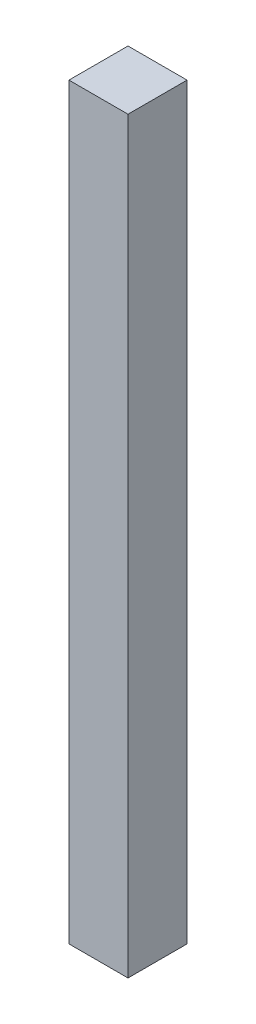
SolidWorks part; units mm, degrees
ref_plane "Front Plane" through (0, 0, 0) normal (0, 0, 1) x (1, 0, 0)
ref_plane "Top Plane" through (0, 0, 0) normal (0, 1, 0) x (1, 0, 0)
ref_plane "Right Plane" through (0, 0, 0) normal (1, 0, 0) x (0, 0, -1)
sketch "Sketch1" plane through (0, 0, 0) normal (0, 1, 0) x (1, 0, 0)
  line L1 (0, 0) -> (15, 0)
  line L2 (0, 0) -> (0, 15)
  line L3 (0, 15) -> (15, 15)
  line L4 (15, 0) -> (15, 15)
  dimension "D1" = 15
extrude "Boss-Extrude1" add sketch "Sketch1" along normal blind 190
